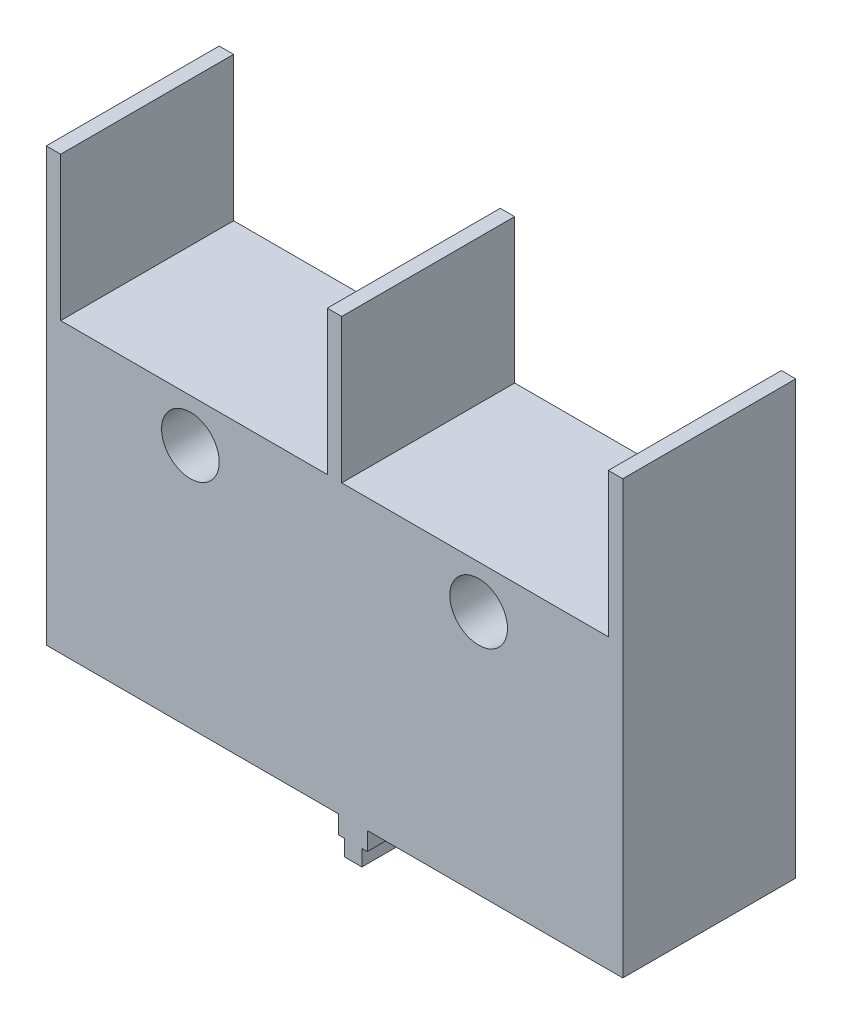
SolidWorks part; units mm, degrees
ref_plane "Plan de face" through (0, 0, 0) normal (0, 0, 1) x (1, 0, 0)
ref_plane "Plan de dessus" through (0, 0, 0) normal (0, 1, 0) x (1, 0, 0)
ref_plane "Plan de droite" through (0, 0, 0) normal (1, 0, 0) x (0, 0, -1)
sketch "Esquisse1" plane through (0, 0, 0) normal (0, 0, 1) x (1, 0, 0)
  line L0 (10.25, 10) -> (19.5, 10)
  line L1 (0, 0) -> (10.14, 0)
  line L2 (0, 0) -> (0, 10)
  line L3 (0.5, 10) -> (9.75, 10)
  line L4 (20, 0) -> (20, 10)
  line L5 (10.14, 0) -> (10.14, -0.6319)
  line L6 (0, 10) -> (0, 15)
  line L7 (0, 15) -> (0.5, 15)
  line L8 (0.5, 10) -> (0.5, 15)
  line L9 (11.1364, -0.6319) -> (11.1364, 0)
  line L10 (10.25, 10) -> (10.25, 15)
  line L11 (10.25, 15) -> (9.75, 15)
  line L12 (9.75, 10) -> (9.75, 15)
  line L13 (10.14, -0.6319) -> (10.3501, -0.6319)
  line L14 (20, 10) -> (20, 15)
  line L15 (20, 15) -> (19.5, 15)
  line L16 (19.5, 10) -> (19.5, 15)
  line L17 (10.3501, -0.6319) -> (10.3501, -1.1903)
  line L18 (10.3501, -1.1903) -> (10.9501, -1.1903)
  line L19 (10.9501, -1.1903) -> (10.9501, -0.6319)
  line L20 (10.9501, -0.6319) -> (11.1364, -0.6319)
  line L21 (11.1364, 0) -> (20, 0)
  circle A0 centre (5, 8.5) radius 1
  circle A1 centre (15, 8.5) radius 1
  dimension "D3" = 2
  dimension "D4" = 2
  dimension "D1" = 10
  dimension "D2" = 20
  dimension "D5" = 5
  dimension "D6" = 10
  dimension "D7" = 8.5
  dimension "D8" = 8.5
  dimension "D9" = 5
  dimension "D10" = 5
  dimension "D11" = 5
  dimension "D12" = 0.6
  dimension "D13" = 0.9964
  dimension "D14" = 0.5
  dimension "D15" = 0.5
  dimension "D16" = 0.5
  dimension "D17" = 9.25
extrude "Boss.-Extru.1" add sketch "Esquisse1" along normal blind 6
